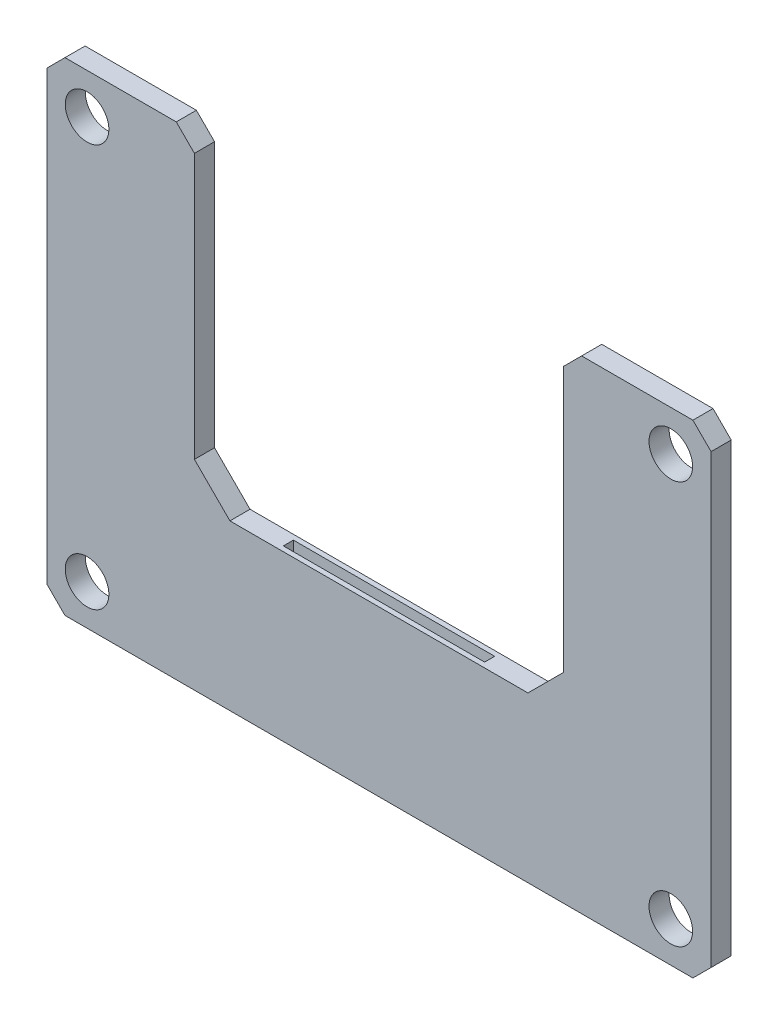
SolidWorks part; units mm, degrees
ref_plane "Front Plane" through (0, 0, 0) normal (0, 0, 1) x (1, 0, 0)
ref_plane "Top Plane" through (0, 0, 0) normal (0, 1, 0) x (1, 0, 0)
ref_plane "Right Plane" through (0, 0, 0) normal (1, 0, 0) x (0, 0, -1)
sketch "Sketch1" plane through (0, 0, 0) normal (0, 0, 1) x (1, 0, 0)
  line L8 (-27.7929, 25) -> (-45.5, 25) construction
  line L11 (-47, 0.5) -> (-3.2071, 0.5) construction
  line L12 (-3.2071, 0.5) -> (-0.5, 3.2071) construction
  line L13 (-0.5, 3.2071) -> (-0.5, 69.7929) construction
  line L14 (-0.5, 69.7929) -> (-3.2071, 72.5) construction
  line L15 (-3.2071, 72.5) -> (-19.7929, 72.5) construction
  line L16 (-19.7929, 72.5) -> (-22.5, 69.7929) construction
  line L17 (-22.5, 69.7929) -> (-22.5, 30.2929) construction
  line L18 (-22.5, 30.2929) -> (-27.7929, 25) construction
  line L21 (-54.5, 25) -> (-72.2071, 25) construction
  line L22 (-72.2071, 25) -> (-77.5, 30.2929) construction
  line L23 (-77.5, 30.2929) -> (-77.5, 69.7929) construction
  line L24 (-77.5, 69.7929) -> (-80.2071, 72.5) construction
  line L25 (-80.2071, 72.5) -> (-96.7929, 72.5) construction
  line L26 (-96.7929, 72.5) -> (-99.5, 69.7929) construction
  line L27 (-99.5, 69.7929) -> (-99.5, 3.2071) construction
  line L28 (-99.5, 3.2071) -> (-96.7929, 0.5) construction
  line L29 (-96.7929, 0.5) -> (-53.7071, 0.5) construction
  line L31 (-27.7929, 25) -> (-45.5, 25)
  line L34 (-50.7602, 0.5) -> (-3.2071, 0.5)
  line L35 (-3.2071, 0.5) -> (-0.5, 3.2071)
  line L36 (-0.5, 3.2071) -> (-0.5, 69.7929)
  line L37 (-0.5, 69.7929) -> (-3.2071, 72.5)
  line L38 (-3.2071, 72.5) -> (-19.7929, 72.5)
  line L39 (-19.7929, 72.5) -> (-22.5, 69.7929)
  line L40 (-22.5, 69.7929) -> (-22.5, 30.2929)
  line L41 (-22.5, 30.2929) -> (-27.7929, 25)
  line L44 (-45.5, 25) -> (-72.2071, 25)
  line L45 (-72.2071, 25) -> (-77.5, 30.2929)
  line L46 (-77.5, 30.2929) -> (-77.5, 69.7929)
  line L47 (-77.5, 69.7929) -> (-80.2071, 72.5)
  line L48 (-80.2071, 72.5) -> (-96.7929, 72.5)
  line L49 (-96.7929, 72.5) -> (-99.5, 69.7929)
  line L50 (-99.5, 69.7929) -> (-99.5, 3.2071)
  line L51 (-99.5, 3.2071) -> (-96.7929, 0.5)
  line L52 (-96.7929, 0.5) -> (-50.7602, 0.5)
  circle A0 centre (-6.5, 66.5) radius 3.25
  circle A1 centre (-6.5, 6.5) radius 3.25
  circle A2 centre (-93.5, 6.5) radius 3.25
  circle A3 centre (-93.5, 66.5) radius 3.25
  circle A4 centre (-93.5, 66.5) radius 4 construction
  point P20 (0, 0)
  dimension "D1" = 6.5
  dimension "D2" = 6.5
  dimension "D3" = 6.5
  dimension "D4" = 6.5
extrude "Boss-Extrude1" add sketch "Sketch1" along normal blind 3
sketch "Sketch2" plane through (0, 0.5, 0) normal (0, -1, 0) x (1, 0, 0)
  line L0 (-96.7929, 3) -> (-3.2071, 3) construction
  line L1 (-35, 0.75) -> (-65, 0.75)
  line L2 (-35, 0.75) -> (-35, 2.25)
  line L3 (-35, 2.25) -> (-65, 2.25)
  line L4 (-65, 0.75) -> (-65, 2.25)
  line L5 (-35, 0.75) -> (-65, 2.25) construction
  line L6 (-35, 2.25) -> (-65, 0.75) construction
  line L7 (-50, 3) -> (-50, -4.6934) construction
  point P0 (-50, 1.5)
  dimension "D1" = 1.5
  dimension "D2" = 1.5
  dimension "D3" = 30
extrude "Cut-Extrude1" cut sketch "Sketch2" against normal up to next
